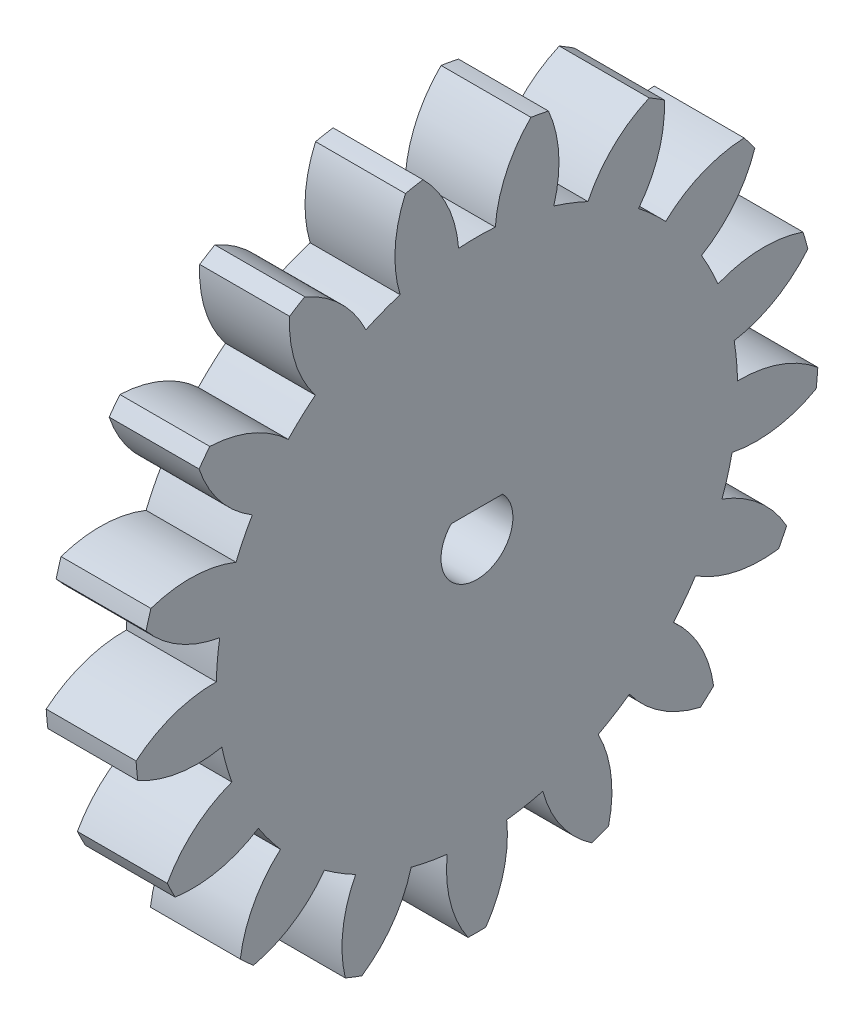
SolidWorks part; units mm, degrees
ref_plane "Plane1" through (0, 0, 0) normal (0, 0, 1) x (1, 0, 0)
ref_plane "Plane2" through (0, 0, 0) normal (0, 1, 0) x (1, 0, 0)
ref_plane "Plane3" through (0, 0, 0) normal (1, 0, 0) x (0, 0, -1)
sketch "HoldingSke" plane through (0, 0, 0) normal (0, 1, 0) x (1, 0, 0)
  line L0 (0, 0) -> (0.4782, -0.1462)
  line L1 (-15, 0) -> (100, 0) construction
  line L2 (0, 0) -> (-2.1039, 2.3779)
  line L3 (0, 0) -> (-11.863, 4.5341)
  line L4 (0, 0) -> (8.2586, 2.5249)
  line L5 (0, 0) -> (-46.8476, -17.4728)
  line L6 (0, 0) -> (-4.1448, -2.7965)
  line L7 (-2.1039, 2.3779) -> (8.6586, 51.2059)
  line L8 (-76.2, 54.61) -> (-75.5, 54.61)
  line L9 (-71.009, 38.7566) -> (-53.1078, 45.2721)
  line L10 (-76.2, 71.12) -> (104.1128, 71.12)
  line L11 (0, 0) -> (-5, 0)
  line L12 (-76.2, 101.6) -> (-76.133, 101.6)
  line L13 (24.9733, 27.94) -> (52.9518, 28.4284)
  line L14 (24.9733, 27.94) -> (24.9743, 27.94)
  line L15 (24.9733, 27.94) -> (100.4006, 29.5858)
  line L16 (-63.627, -2) -> (-12.827, -2)
  circle A0 centre (0, 0) radius 2
  circle A1 centre (0, 0) radius 14.499
  circle A2 centre (0, 0) radius 37.5
  circle A3 centre (0, 0) radius 2
  dimension "MHD" = 28.998
  dimension "Hub_dia" = 75
  dimension "Bore" = 4
  dimension "MBD" = 4
  dimension "Num_teeth" = 17
  dimension "Pitch" = 0.5
  dimension "Overall_len" = 50
  dimension "Show_teeth" = 17
  dimension "Thickness" = 5
  dimension "OAL" = 50.0001
  dimension "T_dim" = 0.7
  dimension "Ap" = 20
  dimension "H" = 19.05
  dimension "Pitch_radius" = 180.3128
  dimension "Width" = 5
  dimension "Backlash" = 0.067
  dimension "Addendum_fac" = 1
  dimension "Dedendum_fac" = 1.25
  dimension "Clearance_fac" = 0.25
  dimension "Dedendum_add" = 0.001
  dimension "Module" = 2
sketch "BasProSke" plane through (0, 0, 0) normal (0, 1, 0) x (1, 0, 0)
  line L0 (-10, 0) -> (60, 0) construction
  line L1 (0, 0) -> (0, 19)
  line L2 (0, 0) -> (5, 0)
  line L3 (5, 0) -> (5, 19)
  line L4 (5, 19) -> (0, 19)
  dimension "Thickness" = 5
  dimension "Diameter" = 38
revolve "Base-Revolve" add sketch "BasProSke" angle 360 about L0
sketch "TooCutSke" plane through (0, 0, 0) normal (1, 0, 0) x (0, 0, -1)
  line L1 (0, 0) -> (0, 107) construction
  line L2 (0, 0) -> (-1.6857, 16.9162) construction
  line L3 (0, 0) -> (-6.2247, 33.2991) construction
  line L4 (-1.6857, 16.9162) -> (-3.1123, 16.6495) construction
  arc A0 (1.0204, 14.4631) -> (-1.0204, 14.4631) centre (0, 0) ccw
  arc A1 (3.0261, 18.7832) -> (-3.0261, 18.7832) centre (0, 0) ccw
  circle A2 centre (0, 0) radius 17 construction
  circle A3 centre (0, 0) radius 15.9748 construction
  arc A4 (-1.0204, 14.4631) -> (-3.0261, 18.7832) centre (-7.8003, 13.9409) ccw
  arc A5 (3.0261, 18.7832) -> (1.0204, 14.4631) centre (7.8003, 13.9409) ccw
  dimension "Root_dia" = 28.998
  dimension "Overcut_dia" = 38.0508
  dimension "Pitch_dia" = 34
  dimension "Base_dia" = 31.9495
  dimension "Flank_rad" = 6.8
  dimension "Half_ang" = 10.588
  dimension "Half_CT" = 1.4513
extrude "ToothCut" cut sketch "TooCutSke" along normal through all
fillet "Breaks" [suppressed] radius 0.04
fillet "RootFillets" [suppressed] radius 0.501
pattern_circular "TeethCuts" count 17 every 21.176 about axis through (-10, 0, 0) along (1, 0, 0) of "ToothCut", "RootFillets", "Breaks"
sketch "HubNeaOneSke" plane through (0, 0, 0) normal (-1, 0, 0) x (0, 0, 1)
  circle A0 centre (0, 0) radius 14.499
  dimension "Diameter" = 28.998
extrude "HubNearOne" [suppressed] add sketch "HubNeaOneSke" along normal blind 45.0001
sketch "HubNeaBotSke" plane through (0, 0, 0) normal (-1, 0, 0) x (0, 0, 1)
  circle A0 centre (0, 0) radius 14.499
  dimension "Diameter" = 28.998
extrude "HubNearBoth" [suppressed] add sketch "HubNeaBotSke" along normal blind 22.5
ref_plane "FarPln" through (5, 0, 0) normal (1, 0, 0) x (0, 0, -1)
sketch "HubFarSke" plane through (5, 0, 0) normal (1, 0, 0) x (0, 0, -1)
  circle A0 centre (0, 0) radius 14.499
  dimension "Diameter" = 28.998
extrude "HubFar" [suppressed] add sketch "HubFarSke" along normal blind 22.5
sketch "BorSke" plane through (0, 0, 0) normal (1, 0, 0) x (0, 0, -1)
  circle A0 centre (0, 0) radius 2
  dimension "Diameter" = 4
extrude "Bore" cut sketch "BorSke" along normal mid plane 100.0001
sketch "KeySke" plane through (0, 0, 0) normal (1, 0, 0) x (0, 0, -1)
  line L0 (-0.8, 0) -> (-0.8, 2.7)
  line L1 (-0.8, 2.7) -> (0.8, 2.7)
  line L2 (0.8, 2.7) -> (0.8, 0)
  line L3 (0, 0) -> (0, 34) construction
  line L4 (-0.8, 0) -> (0.8, 0)
  dimension "Offset" = 2.7
  dimension "Width" = 1.6
extrude "Keyway" [suppressed] cut sketch "KeySke" along normal mid plane 100.0001
pattern_circular "Keyway2" [suppressed] count 2 every 90 about axis through (-10, 0, 0) along (1, 0, 0)
sketch "Sketch1" plane through (5, 0, 0) normal (1, 0, 0) x (0, 0, -1)
  line L0 (-1.4283, 1.4) -> (1.4283, 1.4)
  circle A0 centre (0, 0) radius 2
  circle A1 centre (0, 0) radius 2 construction
  dimension "D1" = 1.4
extrude "Boss-Extrude1" add sketch "Sketch1" against normal blind 5 contours L0 A0
equation "' \"Module@HoldingSke\" = 6.35"
equation "' \"Num_teeth@HoldingSke\" = 12"
equation "' \"Ap@HoldingSke\" =  20"
equation "' \"Ap@HoldingSke\" = 20"
equation "' \"Width@HoldingSke\" = 0.5 * 25.4"
equation "' \"Hub_dia@HoldingSke\"= 1 * 25.4"
equation "' \"Hub_dia@HoldingSke\" = 1 * 25.4"
equation "' \"Overall_len@HoldingSke\" = 1.0 * 25.4"
equation "' \"Bore@HoldingSke\" = 0.75 * 25.4"
equation "' \"T_dim@HoldingSke\" = 0.1 * 25.4"
equation "' \"Width@KeySke\" = 0.25 * 25.4"
equation "' \"Show_teeth@HoldingSke\" = 13"
equation "' \"Backlash@HoldingSke\" = 0.009 * 25.4"
equation "' \"Addendum_fac@HoldingSke\" = 1.0"
equation "' \"Dedendum_fac@HoldingSke\" = 1.25"
equation "' \"Dedendum_add@HoldingSke\" = 0.00005 * 25.4"
equation "' \"Clearance_fac@HoldingSke\" = 0.25"
equation "\"Pitch@HoldingSke\" = 1 / \"Module@HoldingSke\""
equation "\"Overcut_dia@TooCutSke\" = (\"Num_teeth@HoldingSke\" + 2 * \"Addendum_fac@HoldingSke\") / \"Pitch@HoldingSke\" + 0.002 * 25.4"
equation "\"Pitch_dia@TooCutSke\" = \"Num_teeth@HoldingSke\" / \"Pitch@HoldingSke\""
equation "\"Base_dia@TooCutSke\" = \"Num_teeth@HoldingSke\" / \"Pitch@HoldingSke\" * cos((\"Ap@HoldingSke\"  * 3.14159265 / 180))"
equation "\"Root_dia@TooCutSke\" = (\"Num_teeth@HoldingSke\" + 2) / \"Pitch@HoldingSke\" - 2 * (\"Addendum_fac@HoldingSke\" + \"Dedendum_fac@HoldingSke\") / \"Pitch@HoldingSke\" - \"Dedendum_add@HoldingSke\" * 2"
equation "\"Half_ang@TooCutSke\" = 180 / \"Num_teeth@HoldingSke\""
equation "\"Half_CT@TooCutSke\" = \"Num_teeth@HoldingSke\" / \"Pitch@HoldingSke\" * sin((3.14159265 / 2 / \"Num_teeth@HoldingSke\")) / 2 - 7 * \"Backlash@HoldingSke\" / 4"
equation "\"Flank_rad@TooCutSke\" = \"Num_teeth@HoldingSke\" / \"Pitch@HoldingSke\" / 5"
equation "\"Radius@RootFillets\" = \"Clearance_fac@HoldingSke\" / \"Pitch@HoldingSke\" + \"Dedendum_add@HoldingSke\""
equation "\"Break_rad@Breaks\" = 0.02 / \"Pitch@HoldingSke\""
equation "\"Thickness@HoldingSke\" = \"Width@HoldingSke\""
equation "\"OAL@HoldingSke\" = \"Thickness@HoldingSke\""
equation "\"MHD@HoldingSke\" = (\"Num_teeth@HoldingSke\" + 2) / \"Pitch@HoldingSke\" - 2 * (\"Addendum_fac@HoldingSke\" + \"Dedendum_fac@HoldingSke\")  / \"Pitch@HoldingSke\" - \"Dedendum_add@HoldingSke\" * 2"
equation "\"MBD@HoldingSke\" = (\"Num_teeth@HoldingSke\" + 2) / \"Pitch@HoldingSke\" - 2 * (\"Addendum_fac@HoldingSke\" + \"Dedendum_fac@HoldingSke\")  / \"Pitch@HoldingSke\" - \"Dedendum_add@HoldingSke\" * 2 - 0.002 * 25.4"
equation "\"MHD@HoldingSke\" = ((sgn( \"MHD@HoldingSke\" - \"Hub_dia@HoldingSke\" )-1)*( \"MHD@HoldingSke\" - \"Hub_dia@HoldingSke\" ))/-2+ \"Hub_dia@HoldingSke\""
equation "\"MBD@HoldingSke\" = ((sgn( \"MBD@HoldingSke\" - \"Bore@HoldingSke\" )-1)*( \"MBD@HoldingSke\" - \"Bore@HoldingSke\" ))/-2+ \"Bore@HoldingSke\""
equation "\"OAL@HoldingSke\" = ((sgn( \"OAL@HoldingSke\" - \"Overall_len@HoldingSke\" )+1)*( \"OAL@HoldingSke\" - \"Overall_len@HoldingSke\" ))/2 + \"Overall_len@HoldingSke\" + 0.000002 * 25.4"
equation "\"Num_teeth@TeethCuts\" = int( \"Show_teeth@HoldingSke\" ) + 1"
equation "\"Num_teeth@TeethCuts\" = ((sgn( \"Num_teeth@TeethCuts\" - \"Num_teeth@HoldingSke\" )-1)*( \"Num_teeth@TeethCuts\" - \"Num_teeth@HoldingSke\" ))/-2+ \"Num_teeth@HoldingSke\""
equation "\"Num_teeth@TeethCuts\" = ((sgn( \"Num_teeth@TeethCuts\" - 2.0)+1)*( \"Num_teeth@TeethCuts\" - 2.0))/2 +2.0"
equation "\"Angle@TeethCuts\" = 360.0 / \"Num_teeth@HoldingSke\""
equation "\"Diameter@BasProSke\" = (\"Num_teeth@HoldingSke\" + 2 * \"Addendum_fac@HoldingSke\") / \"Pitch@HoldingSke\""
equation "\"Thickness@BasProSke\"  = \"Thickness@HoldingSke\""
equation "' \"Fillet_rad@BasProSke\" =  \"Thickness@HoldingSke\" * 0.05"
equation "' \"Fillet_rad@BasProSke\" = \"Thickness@HoldingSke\" * 0.05"
equation "\"MHD@HoldingSke\" = ((sgn( \"MHD@HoldingSke\" - \"Root_dia@TooCutSke\" )-1)*( \"MHD@HoldingSke\" - \"Root_dia@TooCutSke\" ))/-2+ \"Root_dia@TooCutSke\""
equation "\"Diameter@HubNeaOneSke\" = \"MHD@HoldingSke\""
equation "\"Length@HubNearOne\" = \"OAL@HoldingSke\" - \"Thickness@BasProSke\""
equation "\"Diameter@HubNeaBotSke\" = \"MHD@HoldingSke\""
equation "\"Length@HubNearBoth\" = ( \"OAL@HoldingSke\" - \"Thickness@BasProSke\" ) / 2.0"
equation "\"Thickness@FarPln\" = \"Thickness@BasProSke\""
equation "\"Diameter@HubFarSke\" = \"MHD@HoldingSke\""
equation "\"Length@HubFar\" = ( \"OAL@HoldingSke\" - \"Thickness@BasProSke\" ) / 2.0"
equation "\"Diameter@BorSke\" = \"MBD@HoldingSke\""
equation "\"D1@Bore\" = \"OAL@HoldingSke\" * 2.0"
equation "\"D1@Keyway\" = \"OAL@HoldingSke\" * 2.0"
equation "\"Offset@KeySke\" = \"T_dim@HoldingSke\" + \"MBD@HoldingSke\" / 2.0"
